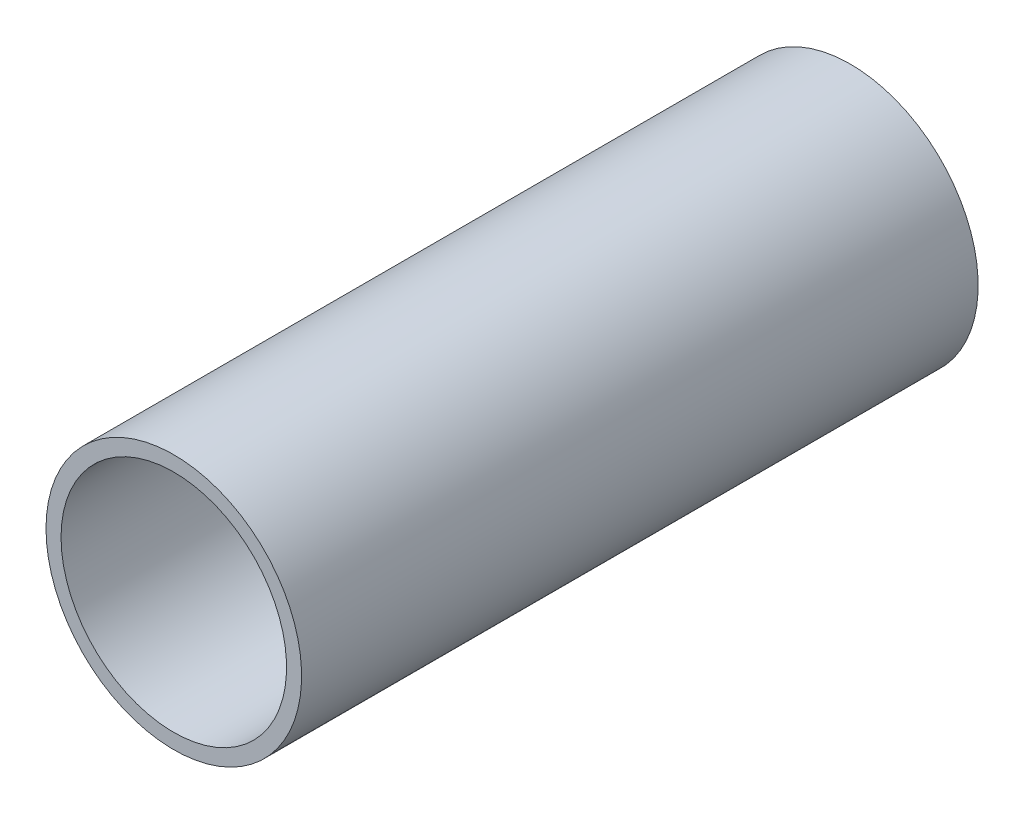
SolidWorks part; units mm, degrees
ref_plane "Front Plane" through (0, 0, 0) normal (0, 0, 1) x (1, 0, 0)
ref_plane "Top Plane" through (0, 0, 0) normal (0, 1, 0) x (1, 0, 0)
ref_plane "Right Plane" through (0, 0, 0) normal (1, 0, 0) x (0, 0, -1)
sketch "Sketch1" plane through (0, 0, 0) normal (0, 0, 1) x (1, 0, 0)
  circle A0 centre (0, 0) radius 15
  circle A1 centre (0, 0) radius 17
  dimension "D1" = 30
  dimension "D2" = 34
extrude "Boss-Extrude1" add sketch "Sketch1" along normal blind 90
